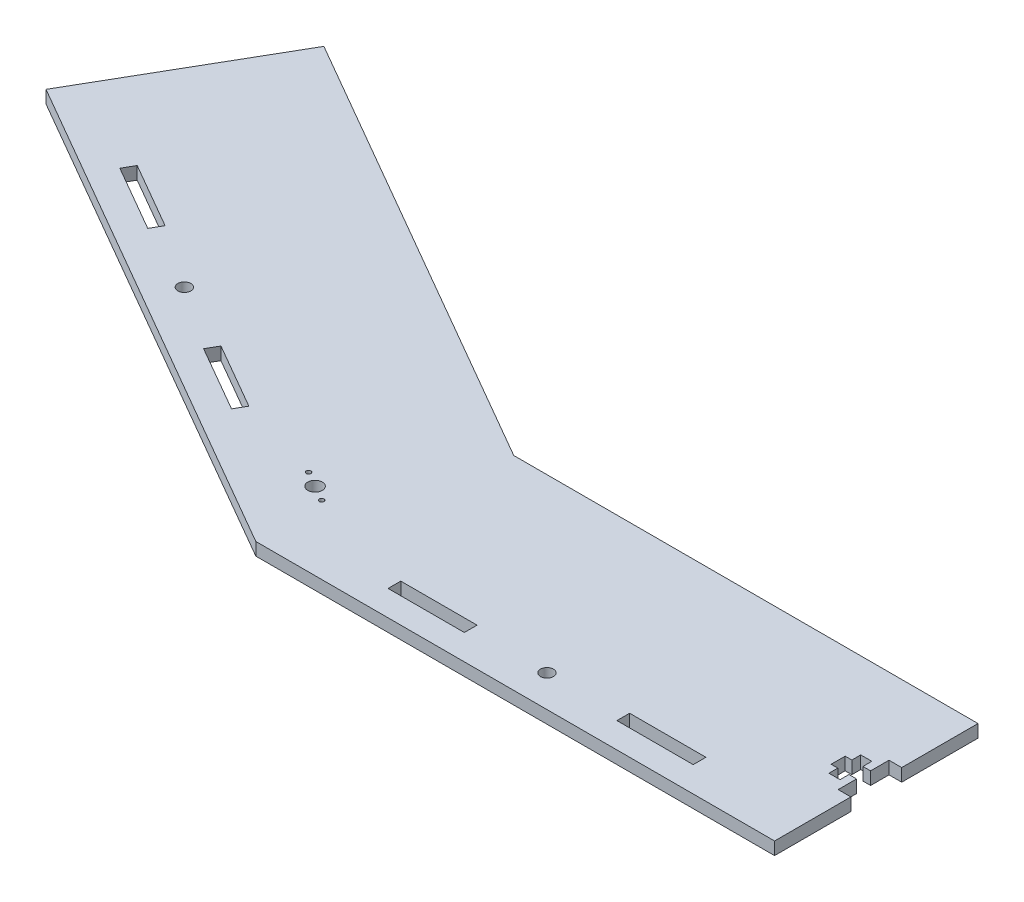
SolidWorks part; units mm, degrees
ref_plane "Front Plane" through (0, 0, 0) normal (0, 0, 1) x (1, 0, 0)
ref_plane "Top Plane" through (0, 0, 0) normal (0, 1, 0) x (1, 0, 0)
ref_plane "Right Plane" through (0, 0, 0) normal (1, 0, 0) x (0, 0, -1)
sketch "Sketch1" plane through (0, 0, 0) normal (0, 1, 0) x (1, 0, 0)
  line L0 (13.6118, 50.8) -> (-11.7882, 6.8059) construction
  line L1 (13.6118, 50.8) -> (129.54, 50.8)
  line L2 (129.54, 50.8) -> (129.54, 31.75)
  line L3 (129.54, 0) -> (0, 0)
  line L4 (0, 0) -> (-123.9731, 71.5759)
  line L5 (-123.9731, 71.5759) -> (-98.5731, 115.57)
  line L6 (-98.5731, 115.57) -> (13.6118, 50.8)
  line L7 (-96.1137, 66.4898) -> (-79.6159, 56.9648)
  line L8 (-96.1137, 66.4898) -> (-97.7012, 63.7402)
  line L9 (-97.7012, 63.7402) -> (-81.2034, 54.2152)
  line L10 (-79.6159, 56.9648) -> (-81.2034, 54.2152)
  line L11 (-46.6204, 37.9148) -> (-30.1226, 28.3898)
  line L12 (-46.6204, 37.9148) -> (-48.2079, 35.1652)
  line L13 (-48.2079, 35.1652) -> (-31.7101, 25.6402)
  line L14 (-30.1226, 28.3898) -> (-31.7101, 25.6402)
  line L15 (-8.3987, 21.5667) -> (-0.6997, 17.1217) construction
  line L16 (-80.4097, 55.59) -> (-47.4141, 36.54) construction
  line L17 (0, 0) -> (-0.0331, 0.1029) construction
  line L18 (26.67, 9.525) -> (45.72, 9.525)
  line L19 (26.67, 9.525) -> (26.67, 6.35)
  line L20 (26.67, 6.35) -> (45.72, 6.35)
  line L21 (45.72, 9.525) -> (45.72, 6.35)
  line L22 (83.82, 9.525) -> (102.87, 9.525)
  line L23 (83.82, 9.525) -> (83.82, 6.35)
  line L24 (83.82, 6.35) -> (102.87, 6.35)
  line L25 (102.87, 9.525) -> (102.87, 6.35)
  line L26 (45.72, 7.9375) -> (83.82, 7.9375) construction
  line L28 (121.6819, 23.6474) -> (121.6819, 21.4313)
  line L29 (129.54, 31.75) -> (126.365, 31.75)
  line L30 (129.54, 31.75) -> (129.54, 19.05) construction
  line L31 (129.54, 19.05) -> (126.365, 19.05)
  line L32 (126.365, 31.75) -> (126.365, 27.1526)
  line L33 (124.46, 27.1526) -> (126.365, 27.1526)
  line L34 (129.54, 19.05) -> (129.54, 0)
  line L35 (124.46, 23.6474) -> (126.365, 23.6474)
  line L36 (129.54, 25.4) -> (120.015, 25.4) construction
  line L37 (121.6819, 29.3688) -> (124.46, 29.3688)
  line L38 (121.6819, 29.3688) -> (121.6819, 27.1526)
  line L39 (121.6819, 21.4313) -> (124.46, 21.4313)
  line L40 (124.46, 29.3688) -> (124.46, 27.1526)
  line L41 (120.015, 27.1526) -> (121.6819, 27.1526)
  line L42 (120.015, 27.1526) -> (120.015, 23.6474)
  line L43 (120.015, 23.6474) -> (121.6819, 23.6474)
  line L45 (124.46, 23.6474) -> (124.46, 21.4313)
  line L46 (126.365, 23.6474) -> (126.365, 19.05)
  circle A0 centre (-8.3987, 21.5667) radius 0.5842
  circle A1 centre (-4.5492, 19.3442) radius 1.8161
  circle A2 centre (-0.6997, 17.1217) radius 0.5842
  circle A3 centre (-63.9119, 46.065) radius 1.6256
  circle A4 centre (64.77, 7.9375) radius 1.6256
  dimension "D7" = 3.175
  dimension "D8" = 4.953
  dimension "D9" = 26.67
  dimension "D15" = 3.6322
  dimension "D16" = 1.1684
  dimension "D17" = 8.89
  dimension "D25" = 12.7
  dimension "D34" = 6.35
  dimension "D22" = 3.2512
  dimension "D35" = 3.2512
  dimension "D2" = 50.8
  dimension "D3" = 150
  dimension "D4" = 50.8
  dimension "D5" = 150
  dimension "D6" = 129.54
  dimension "D10" = 19.05
  dimension "D11" = 19.05
  dimension "D12" = 3.175
  dimension "D13" = 6.35
  dimension "D14" = 26.67
  dimension "D18" = 19.05
  dimension "D19" = 3.175
  dimension "D20" = 19.05
  dimension "D21" = 3.175
  dimension "D23" = 26.67
  dimension "D24" = 26.67
  dimension "D26" = 129.54
  dimension "D27" = 3.5052
  dimension "D28" = 7.9375
  dimension "D29" = 3.175
  dimension "D30" = 1.905
  dimension "D31" = 2.7781
  dimension "D32" = 9.525
  dimension "D33" = 25.4
extrude "Boss-Extrude2" add sketch "Sketch1" along normal blind 3.175
